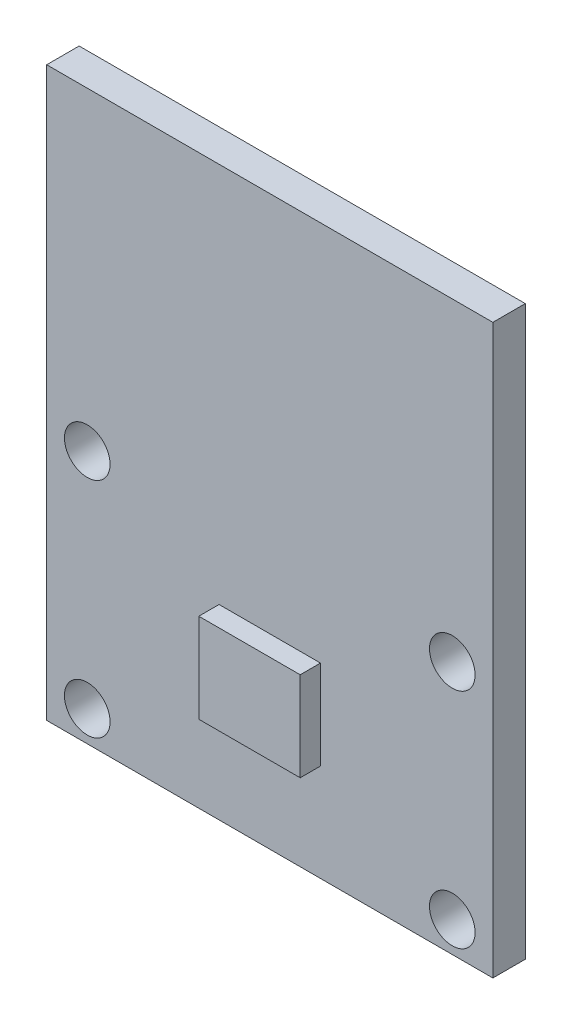
SolidWorks part; units mm, degrees
ref_plane "Front Plane" through (0, 0, 0) normal (0, 0, 1) x (1, 0, 0)
ref_plane "Top Plane" through (0, 0, 0) normal (0, 1, 0) x (1, 0, 0)
ref_plane "Right Plane" through (0, 0, 0) normal (1, 0, 0) x (0, 0, -1)
sketch "Sketch1" plane through (0, 0, 0) normal (0, 0, 1) x (1, 0, 0)
  line L1 (0, 0) -> (22, 0)
  line L2 (0, 0) -> (0, 28)
  line L3 (0, 28) -> (22, 28)
  line L4 (22, 0) -> (22, 28)
  dimension "D1" = 22
  dimension "D2" = 28
extrude "Boss-Extrude1" add sketch "Sketch1" along normal blind 1.6
sketch "Sketch3" plane through (0, 0, 1.6) normal (0, 0, 1) x (1, 0, 0)
  line L0 (0, 28) -> (0, 0) construction
  line L1 (0, 0) -> (22, 0) construction
  circle A0 centre (2, 1.5) radius 1.125
  circle A1 centre (2, 12.5) radius 1.125
  circle A2 centre (20, 1.5) radius 1.125
  circle A3 centre (20, 12.5) radius 1.125
  dimension "D1" = 2
  dimension "D3" = 2
  dimension "D5" = 18
  dimension "D7" = 18
  dimension "D2" = 1.5
  dimension "D4" = 11
  dimension "D6" = 1.5
  dimension "D8" = 11
extrude "Cut-Extrude1" cut sketch "Sketch3" against normal through all contours A1 | A3 | A0 | A2
sketch "Sketch4" plane through (0, 0, 1.6) normal (0, 0, 1) x (1, 0, 0)
  line L1 (20, 1.5) -> (20, 12.5)
  line L2 (0, 0) -> (22, 0) construction
  line L4 (8.5, 9.2) -> (13.5, 9.2)
  line L5 (8.5, 9.2) -> (8.5, 4.8)
  line L6 (8.5, 4.8) -> (13.5, 4.8)
  line L7 (13.5, 9.2) -> (13.5, 4.8)
  line L8 (0, 28) -> (0, 0) construction
  dimension "D1" = 5
  dimension "D2" = 4.4
  dimension "D3" = 9.2
  dimension "D4" = 8.5
extrude "Boss-Extrude2" add sketch "Sketch4" along normal blind 1 contours L5 L4 L7 L6
